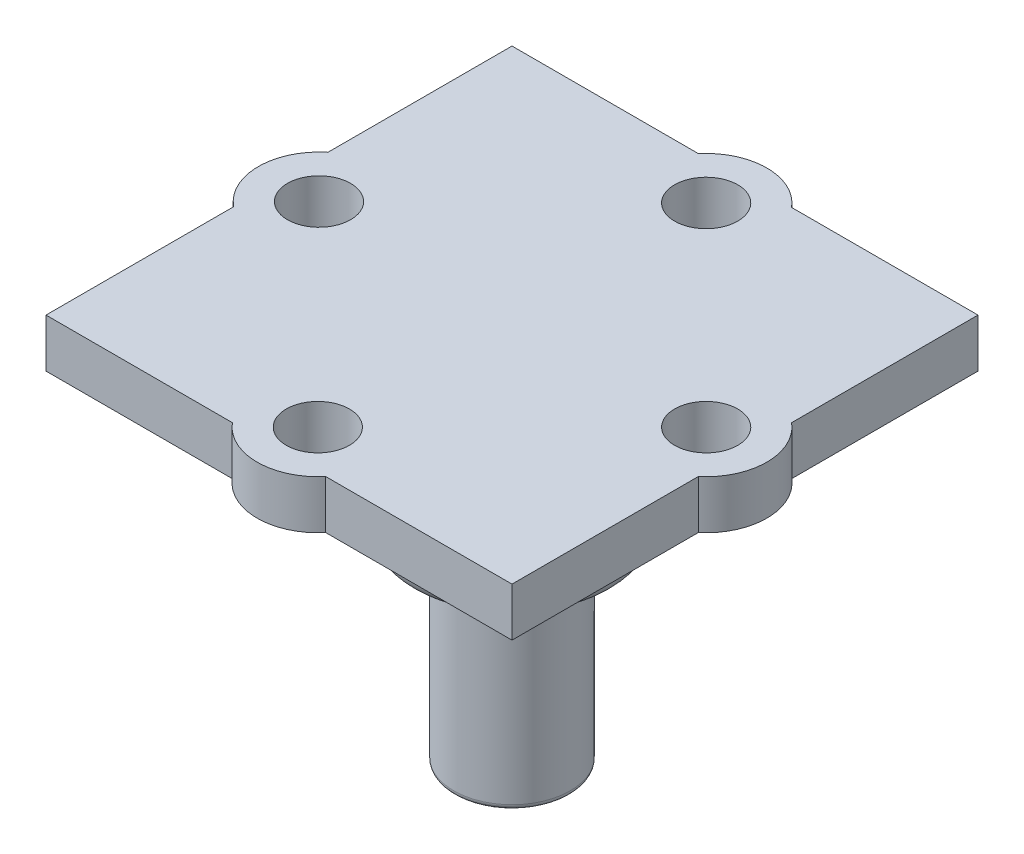
SolidWorks part; units mm, degrees
ref_plane "Спереди" through (0, 0, 0) normal (0, 0, 1) x (1, 0, 0)
ref_plane "Сверху" through (0, 0, 0) normal (0, 1, 0) x (1, 0, 0)
ref_plane "Справа" through (0, 0, 0) normal (1, 0, 0) x (0, 0, -1)
sketch "Sketch1" plane through (0, 0, 0) normal (0, 1, 0) x (1, 0, 0)
  line L0 (-24, -4.6689) -> (-24, -24)
  line L1 (-24, 24) -> (-4.8023, 24)
  line L2 (-24, 24) -> (-24, 5.0436)
  line L3 (-24, -24) -> (-4.8023, -24)
  line L4 (24, 24) -> (24, 4.8023)
  line L5 (-24, 24) -> (24, -24) construction
  line L6 (-24, -24) -> (24, 24) construction
  line L7 (-16, 16) -> (-4.8023, 16)
  line L8 (-16, 16) -> (-16, 4.9342)
  line L9 (-16, -16) -> (-4.8023, -16)
  line L10 (16, 16) -> (16, 4.8023)
  line L11 (-16, 16) -> (16, -16) construction
  line L12 (-16, -16) -> (16, 16) construction
  line L13 (-16, -4.5595) -> (-16, -16)
  line L14 (4.8023, 16) -> (16, 16)
  line L15 (4.8023, 24) -> (24, 24)
  line L16 (16, -4.8023) -> (16, -16)
  line L17 (4.8023, -16) -> (16, -16)
  line L18 (4.8023, -24) -> (24, -24)
  line L19 (24, -4.8023) -> (24, -24)
  circle A0 centre (-20.0657, 0.1873) radius 3.25
  circle A1 centre (0, 20) radius 3.25
  circle A2 centre (20, 0) radius 3.25
  circle A3 centre (0, -20) radius 3.25
  arc A4 (12, -16) -> (6.1732, -19.0234) centre (0, 0) ccw construction
  arc A5 (-24, 5.0436) -> (-24, -4.6689) centre (-20.0657, 0.1873) ccw
  arc A6 (-4.8023, 16) -> (4.8023, 16) centre (0, 20) ccw
  arc A7 (16, 4.8023) -> (16, -4.8023) centre (20, 0) ccw
  arc A8 (4.8023, -16) -> (-4.8023, -16) centre (0, -20) ccw
  arc A9 (-16, -4.5595) -> (-16, 4.9342) centre (-20.0657, 0.1873) ccw
  arc A10 (4.8023, 24) -> (-4.8023, 24) centre (0, 20) ccw
  arc A11 (24, -4.8023) -> (24, 4.8023) centre (20, 0) ccw
  arc A12 (-4.8023, -24) -> (4.8023, -24) centre (0, -20) ccw
  point P0 (0, 0)
  point P6 (0, 0)
  dimension "D3" = 40
  dimension "D4" = 6.5
  dimension "D5" = 12.5
  dimension "D6" = 6.5
  dimension "D7" = 12.5
  dimension "D8" = 6.5
  dimension "D9" = 12.5
  dimension "D10" = 6.5
  dimension "D11" = 12.5
  dimension "D1" = 48
  dimension "D2" = 32
  dimension "D12" = 32
extrude "Boss-Extrude1" add sketch "Sketch1" along normal blind 5 contours L4 A11 L19 L18 A12 L3 L0 A5 L2 L1 A10 L15 | A8 L9 L13 A9 L8 L7 A6 L14 L10 A7 L16 L17 | A1 | A3 | A2 | A0
ref_plane "Plane1" through (0, -65, 0) normal (0, -1, 0) x (-1, 0, 0)
sketch "Sketch2" plane through (0, 0, 0) normal (0, -1, 0) x (1, 0, 0)
  line L1 (-16.3247, -16.4535) -> (16.3247, -16.4535)
  line L2 (-16.3247, -16.4535) -> (-16.3247, 16.4535)
  line L3 (-16.3247, 16.4535) -> (16.3247, 16.4535)
  line L4 (16.3247, -16.4535) -> (16.3247, 16.4535)
  line L5 (-16.3247, -16.4535) -> (16.3247, 16.4535) construction
  line L6 (-16.3247, 16.4535) -> (16.3247, -16.4535) construction
  point P0 (0, 0)
extrude "Boss-Extrude2" add sketch "Sketch2" against normal up to surface (5 mm away) up to face at (20, 5, 3.25)
sketch "Sketch3" plane through (0, 0, 0) normal (0, -1, 0) x (-1, 0, 0)
  circle A0 centre (0, 0) radius 10.5672
extrude "Boss-Extrude3" add sketch "Sketch3" along normal blind 15
sketch "Sketch4" plane through (0, -15, 0) normal (0, -1, 0) x (-1, 0, 0)
  circle A0 centre (0, 0) radius 6
extrude "Boss-Extrude4" add sketch "Sketch4" along normal blind 20
fillet "Fillet1" radius 2 3 edges at (0, -15, -6) (0, 0, 10.5672) (0, -15, -10.5672)
fillet "Fillet2" radius 0.56 1 edges at (0, -35, -6)
